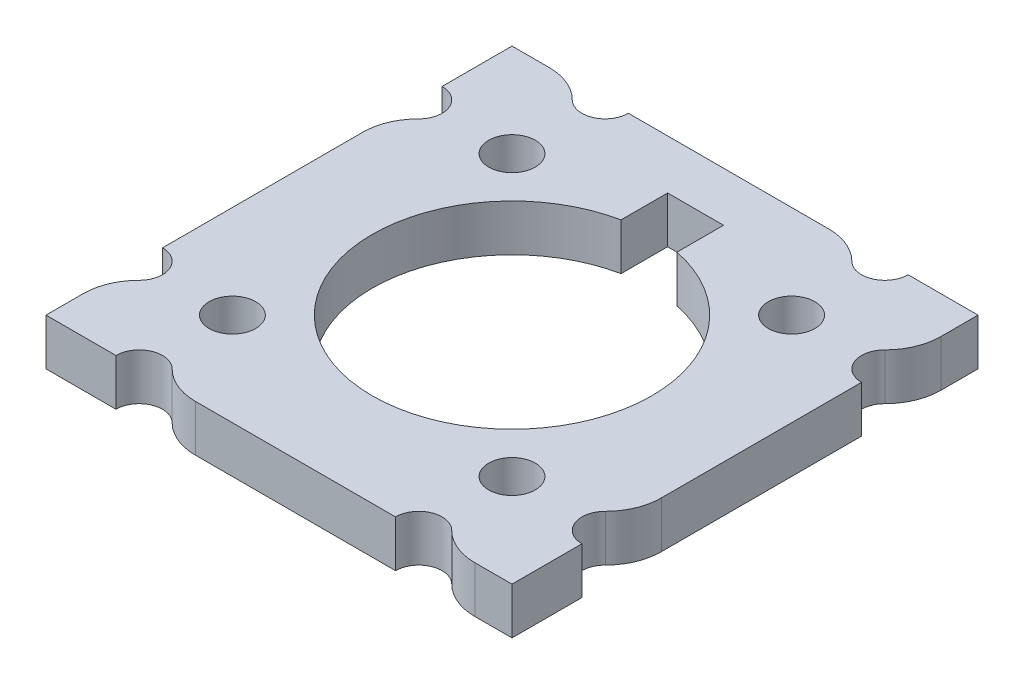
SolidWorks part; units mm, degrees
ref_plane "Front Plane" through (0, 0, 0) normal (0, 0, 1) x (1, 0, 0)
ref_plane "Top Plane" through (0, 0, 0) normal (0, 1, 0) x (1, 0, 0)
ref_plane "Right Plane" through (0, 0, 0) normal (1, 0, 0) x (0, 0, -1)
sketch "Sketch1" plane through (0, 0, 0) normal (0, 1, 0) x (1, 0, 0)
  line L0 (0, 0) -> (0, 35.7255) construction
  line L1 (-25, 25) -> (25, 25)
  line L2 (-25, 25) -> (-25, -25)
  line L3 (-25, -25) -> (25, -25)
  line L4 (25, 25) -> (25, -25)
  line L5 (-25, 25) -> (25, -25) construction
  line L6 (-25, -25) -> (25, 25) construction
  line L7 (0, 0) -> (59.1801, 0) construction
  circle A0 centre (15, 15) radius 2.5
  circle A1 centre (15, -15) radius 2.5
  circle A2 centre (-15, -15) radius 2.5
  circle A3 centre (-15, 15) radius 2.5
  point P0 (0, 0)
  point P12 (0, 0)
  point P18 (0, 0)
  point P19 (0, 0)
  point P20 (-15, -15)
  point P21 (-15, -15)
  point P22 (-15, -15)
  point P23 (-15, -6.5205)
  point P24 (15, -15)
  point P25 (0, 0)
  point P26 (0, 0)
  point P27 (15, -15)
  point P28 (-15, -15)
  point P29 (-15, -15)
  point P30 (0, 0)
  point P31 (-15, -15)
  dimension "D5" = 5
  dimension "D1" = 50
  dimension "D2" = 50
  dimension "D3" = 30
  dimension "D4" = 30
extrude "Boss-Extrude1" add sketch "Sketch1" along normal blind 5
sketch "Sketch2" plane through (0, 5, 0) normal (0, 1, 0) x (1, 0, 0)
  line L0 (25, -25) -> (25, 25) construction
  line L1 (15, 15) -> (25, 15) construction
  line L2 (15, -15) -> (25, -15) construction
  line L3 (-25, 25) -> (-25, -25) construction
  line L4 (25, 25) -> (-25, 25) construction
  line L5 (-15, 15) -> (-15, 25) construction
  line L6 (0, 0) -> (39.8002, 0) construction
  line L7 (0, 0) -> (0, 34.0211) construction
  circle A0 centre (25, 15) radius 2.5
  circle A1 centre (25, -15) radius 2.5
  circle A2 centre (-25, 15) radius 2.5
  circle A3 centre (-25, -15) radius 2.5
  circle A4 centre (-15, 25) radius 2.5
  circle A5 centre (15, 25) radius 2.5
  circle A6 centre (15, -25) radius 2.5
  circle A7 centre (-15, -25) radius 2.5
  dimension "D1" = 5
  dimension "D2" = 2
extrude "Cut-Extrude1" cut sketch "Sketch2" against normal blind 5
sketch "Sketch3" plane through (0, 5, 0) normal (0, 1, 0) x (1, 0, 0)
  line L0 (0, 0) -> (0, 22.2372) construction
  line L1 (-3, 19.6969) -> (3, 19.6969)
  line L2 (-3, 19.6969) -> (-3, 14.6969)
  line L4 (3, 19.6969) -> (3, 14.6969)
  arc A0 (-3, 14.6969) -> (3, 14.6969) centre (0, 0) ccw
  dimension "D1" = 30
  dimension "D2" = 5
  dimension "D3" = 6
extrude "Cut-Extrude2" cut sketch "Sketch3" against normal through all
fillet "Fillet1" radius 6 8 edges at (-12.5, 2.5, 25) (-25, 2.5, 17.5) (-25, 2.5, -12.5) (-17.5, 2.5, -25) (12.5, 2.5, -25) (25, 2.5, -17.5) (25, 2.5, 12.5) (17.5, 2.5, 25)
